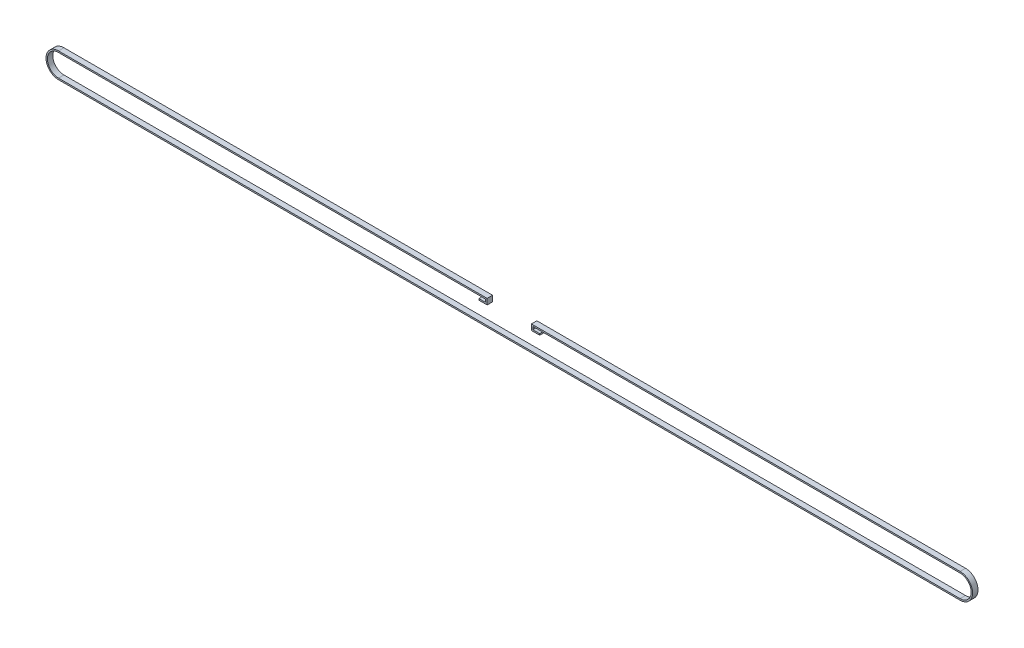
SolidWorks part; units mm, degrees
ref_plane "Frontal Plane" through (0, 0, 0) normal (0, 0, 1) x (1, 0, 0)
ref_plane "Horizontal Plane" through (0, 0, 0) normal (0, 1, 0) x (1, 0, 0)
ref_plane "Profile Plane" through (0, 0, 0) normal (1, 0, 0) x (0, 0, -1)
sketch "Sketch1" plane through (0, 0, 0) normal (0, 0, 1) x (1, 0, 0)
  line L0 (-790, -19.4056) -> (790, -19.4056)
  line L1 (790, 19.4056) -> (-790, 19.4056)
  line L2 (-790, 21.9056) -> (790, 21.9056)
  line L3 (790, -21.9056) -> (-790, -21.9056)
  arc A0 (790, -19.4056) -> (790, 19.4056) centre (790, 0) ccw
  arc A1 (-790, 19.4056) -> (-790, -19.4056) centre (-790, 0) ccw
  arc A2 (790, 21.9056) -> (790, -21.9056) centre (790, 0) cw
  arc A3 (-790, -21.9056) -> (-790, 21.9056) centre (-790, 0) cw
  point P3 (0, -19.4056)
  point P8 (0, 19.4056)
  point P12 (0, 21.9056)
  dimension "D1" = 19.4056
  dimension "D2" = 1580
  dimension "D3" = 2.5
extrude "Boss-Extrude1" add sketch "Sketch1" along normal mid plane 9.525
sketch "Sketch2" plane through (0, 0, 0) normal (0, 0, 1) x (1, 0, 0)
  line L1 (-40, 21.9056) -> (40, 21.9056)
  line L2 (-40, 21.9056) -> (-40, 19.4056)
  line L3 (-40, 19.4056) -> (40, 19.4056)
  line L4 (40, 21.9056) -> (40, 19.4056)
  line L5 (-40, 21.9056) -> (40, 19.4056) construction
  line L6 (-40, 19.4056) -> (40, 21.9056) construction
  line L7 (790, 21.9056) -> (-790, 21.9056) construction
  point P0 (0, 20.6556)
  dimension "D1" = 2.5
  dimension "D2" = 80
extrude "Cut-Extrude1" cut sketch "Sketch2" against normal mid plane 9.525
sketch "Sketch3" plane through (0, 0, 4.7625) normal (0, 0, 1) x (1, 0, 0)
  line L0 (-41.25, 21.9056) -> (-38.75, 21.9056)
  line L8 (-41.25, 21.9056) -> (-41.25, 14.4056)
  line L9 (-41.25, 14.4056) -> (-53.25, 14.4056)
  line L10 (-53.25, 14.4056) -> (-53.25, 11.9056)
  line L11 (-53.25, 11.9056) -> (-38.75, 11.9056)
  line L12 (-38.75, 11.9056) -> (-38.75, 21.9056)
  line L13 (-40, 19.4056) -> (-790, 19.4056) construction
  line L14 (0, 5.8446) -> (0, 38.3639) construction
  line L15 (53.25, 11.9056) -> (38.75, 11.9056)
  line L16 (53.25, 14.4056) -> (53.25, 11.9056)
  line L17 (41.25, 14.4056) -> (53.25, 14.4056)
  line L18 (41.25, 21.9056) -> (41.25, 14.4056)
  line L19 (41.25, 21.9056) -> (38.75, 21.9056)
  line L20 (38.75, 11.9056) -> (38.75, 21.9056)
  point P7 (-40, 21.9056)
  dimension "D1" = 2.5
  dimension "D2" = 5
  dimension "D3" = 12
  dimension "D4" = 2.5
extrude "Boss-Extrude2" add sketch "Sketch3" against normal blind 9.525
equation "\"BaseL\"= 6ft"
equation "\"BaseW\"= 5.5in"
equation "\"BaseThickness\"= 1in"
equation "\"RailGap\"= 4cm"
equation "\"SlidePlateL\"= 8cm"
equation "\"SlidePlateW\"= 11cm"
equation "\"SlidePlateThickness\"= 5mm"
equation "\"SlidePlateClearance\"= 1cm"
equation "\"BoxThickness\"= .5cm"
equation "\"BoxX\"= \"RailGap\" + 30mm"
equation "\"BoxH\"= 2cm + \"SlidePlateClearance\" + \"SlidePlateThickness\" + 3cm"
equation "\"BeltW\"= .375in"
equation "\"PulleyRadius\"= 15.1mm"
equation "\"PulleyH\"= 30mm + 21.4056mm - 2.5mm"
equation "\"PulleyShaftDiameter\"= .3125in"
equation "\"PulleyShaftL\"= 4in"
equation "\"PulleyShaft2L\"= 3in"
equation "\"MotorL\"= 4.43in"
equation "\"MotorRadius\"= 1.291in"
equation "\"MotorShaftRadius\"= .15625in"
equation "\"MotorShaftL\"= 1.75in"
equation "\"HeadstoneThickness\"= 7.5mm"
equation "\"BeltL\"= 1500mm + \"80\""
equation "\"BeltThickness\"= 2.5mm"
equation "\"D2@Sketch1\"=\"BeltL\""
equation "\"D3@Sketch1\"=\"BeltThickness\""
equation "\"D1@Boss-Extrude1\"=\"BeltW\""
equation "\"D1@Sketch2\"=\"BeltThickness\""
equation "\"D2@Sketch2\"=\"SlidePlateL\"- 0cm"
equation "\"D1@Cut-Extrude1\"=\"BeltW\""
equation "\"D1@Boss-Extrude2\"=\"BeltW\""
